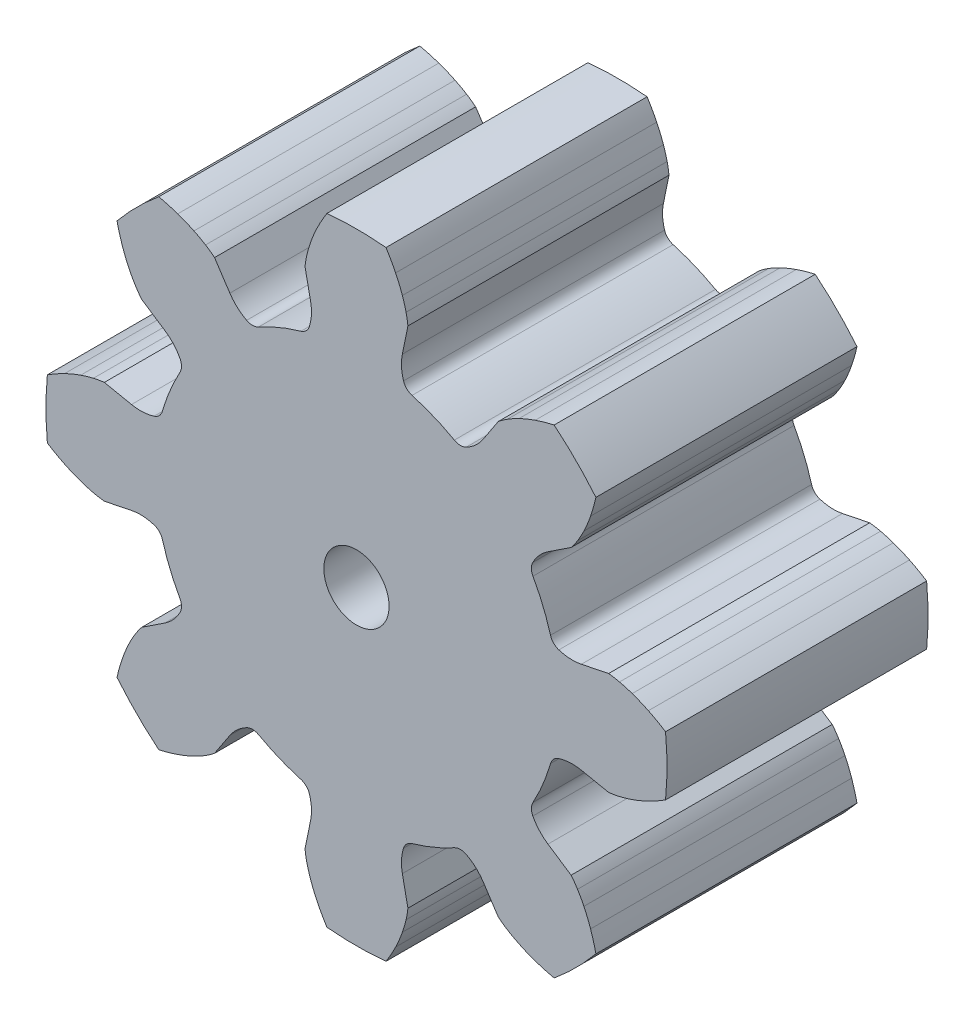
SolidWorks part; units mm, degrees
ref_plane "Front Plane" through (0, 0, 0) normal (0, 0, 1) x (1, 0, 0)
ref_plane "Top Plane" through (0, 0, 0) normal (0, 1, 0) x (1, 0, 0)
ref_plane "Right Plane" through (0, 0, 0) normal (1, 0, 0) x (0, 0, -1)
sketch "Model" plane through (0, 0, 0) normal (0, 0, 1) x (1, 0, 0)
  line L0 (10.9417, -2.2327) -> (12.2644, -2.5026)
  line L1 (12.2644, 2.5026) -> (10.9417, 2.2327)
  line L2 (9.3157, 6.1582) -> (10.4419, 6.9027)
  line L3 (6.9027, 10.4419) -> (6.1582, 9.3157)
  line L4 (2.2327, 10.9417) -> (2.5026, 12.2644)
  line L5 (-2.5026, 12.2644) -> (-2.2327, 10.9417)
  line L6 (-6.1582, 9.3157) -> (-6.9027, 10.4419)
  line L7 (-10.4419, 6.9027) -> (-9.3157, 6.1582)
  line L8 (-10.9417, 2.2327) -> (-12.2644, 2.5026)
  line L9 (-12.2644, -2.5026) -> (-10.9417, -2.2327)
  line L10 (-9.3157, -6.1582) -> (-10.4419, -6.9027)
  line L11 (-6.9027, -10.4419) -> (-6.1582, -9.3157)
  line L12 (-2.2327, -10.9417) -> (-2.5026, -12.2644)
  line L13 (2.5026, -12.2644) -> (2.2327, -10.9417)
  line L14 (6.1582, -9.3157) -> (6.9027, -10.4419)
  line L15 (10.4419, -6.9027) -> (9.3157, -6.1582)
  arc A1 (9.072, -3.7577) -> (9.44, -2.7033) centre (0, 0) ccw
  arc A2 (9.8442, -2.2889) -> (9.44, -2.7033) centre (10.0267, -2.8713) ccw
  arc A3 (10.9417, -2.2327) -> (9.8442, -2.2889) centre (10.502, -4.3879) ccw
  arc A4 (12.2644, -2.5026) -> (12.7952, -2.4127) centre (11.8124, 1.7812) ccw
  arc A5 (12.7952, -2.4127) -> (13.4129, -2.2334) centre (11.3922, 3.5743) ccw
  arc A6 (13.4129, -2.2334) -> (14.2001, -1.9047) centre (11.1046, 4.4008) ccw
  arc A7 (14.2001, -1.9047) -> (15.0358, -1.4368) centre (10.2968, 6.0465) ccw
  arc A8 (15.0358, -1.4368) -> (15.0358, 1.4368) centre (0, 0) ccw
  arc A9 (15.0358, 1.4368) -> (14.2001, 1.9047) centre (10.2968, -6.0465) ccw
  arc A10 (14.2001, 1.9047) -> (13.4129, 2.2334) centre (11.1046, -4.4008) ccw
  arc A11 (13.4129, 2.2334) -> (12.7952, 2.4127) centre (11.3922, -3.5743) ccw
  arc A12 (12.7952, 2.4127) -> (12.2644, 2.5026) centre (11.8124, -1.7812) ccw
  arc A13 (9.8442, 2.2889) -> (10.9417, 2.2327) centre (10.502, 4.3879) ccw
  arc A14 (9.44, 2.7033) -> (9.8442, 2.2889) centre (10.0267, 2.8713) ccw
  arc A15 (9.44, 2.7033) -> (8.5866, 4.7635) centre (0, 0) ccw
  arc A16 (8.5794, 5.3424) -> (8.5866, 4.7635) centre (9.1203, 5.0596) ccw
  arc A17 (9.3157, 6.1582) -> (8.5794, 5.3424) centre (10.5287, 4.3233) ccw
  arc A18 (10.4419, 6.9027) -> (10.7537, 7.3415) centre (7.0931, 9.6121) ccw
  arc A19 (10.7537, 7.3415) -> (11.0637, 7.9051) centre (5.5281, 10.5829) ccw
  arc A20 (11.0637, 7.9051) -> (11.3878, 8.6941) centre (4.7403, 10.964) ccw
  arc A21 (11.3878, 8.6941) -> (11.6479, 9.616) centre (3.0054, 11.5564) ccw
  arc A22 (11.6479, 9.616) -> (9.616, 11.6479) centre (0, 0) ccw
  arc A23 (9.616, 11.6479) -> (8.6941, 11.3878) centre (11.5564, 3.0054) ccw
  arc A24 (8.6941, 11.3878) -> (7.9051, 11.0637) centre (10.964, 4.7403) ccw
  arc A25 (7.9051, 11.0637) -> (7.3415, 10.7537) centre (10.5829, 5.5281) ccw
  arc A26 (7.3415, 10.7537) -> (6.9027, 10.4419) centre (9.6121, 7.0931) ccw
  arc A27 (5.3424, 8.5794) -> (6.1582, 9.3157) centre (4.3233, 10.5287) ccw
  arc A28 (4.7635, 8.5866) -> (5.3424, 8.5794) centre (5.0596, 9.1203) ccw
  arc A29 (4.7635, 8.5866) -> (2.7033, 9.44) centre (0, 0) ccw
  arc A30 (2.2889, 9.8442) -> (2.7033, 9.44) centre (2.8713, 10.0267) ccw
  arc A31 (2.2327, 10.9417) -> (2.2889, 9.8442) centre (4.3879, 10.502) ccw
  arc A32 (2.5026, 12.2644) -> (2.4127, 12.7952) centre (-1.7812, 11.8124) ccw
  arc A33 (2.4127, 12.7952) -> (2.2334, 13.4129) centre (-3.5743, 11.3922) ccw
  arc A34 (2.2334, 13.4129) -> (1.9047, 14.2001) centre (-4.4008, 11.1046) ccw
  arc A35 (1.9047, 14.2001) -> (1.4368, 15.0358) centre (-6.0465, 10.2968) ccw
  arc A36 (1.4368, 15.0358) -> (-1.4368, 15.0358) centre (0, 0) ccw
  arc A37 (-1.4368, 15.0358) -> (-1.9047, 14.2001) centre (6.0465, 10.2968) ccw
  arc A38 (-1.9047, 14.2001) -> (-2.2334, 13.4129) centre (4.4008, 11.1046) ccw
  arc A39 (-2.2334, 13.4129) -> (-2.4127, 12.7952) centre (3.5743, 11.3922) ccw
  arc A40 (-2.4127, 12.7952) -> (-2.5026, 12.2644) centre (1.7812, 11.8124) ccw
  arc A41 (-2.2889, 9.8442) -> (-2.2327, 10.9417) centre (-4.3879, 10.502) ccw
  arc A42 (-2.7033, 9.44) -> (-2.2889, 9.8442) centre (-2.8713, 10.0267) ccw
  arc A43 (-2.7033, 9.44) -> (-4.7635, 8.5866) centre (0, 0) ccw
  arc A44 (-5.3424, 8.5794) -> (-4.7635, 8.5866) centre (-5.0596, 9.1203) ccw
  arc A45 (-6.1582, 9.3157) -> (-5.3424, 8.5794) centre (-4.3233, 10.5287) ccw
  arc A46 (-6.9027, 10.4419) -> (-7.3415, 10.7537) centre (-9.6121, 7.0931) ccw
  arc A47 (-7.3415, 10.7537) -> (-7.9051, 11.0637) centre (-10.5829, 5.5281) ccw
  arc A48 (-7.9051, 11.0637) -> (-8.6941, 11.3878) centre (-10.964, 4.7403) ccw
  arc A49 (-8.6941, 11.3878) -> (-9.616, 11.6479) centre (-11.5564, 3.0054) ccw
  arc A50 (-9.616, 11.6479) -> (-11.6479, 9.616) centre (0, 0) ccw
  arc A51 (-11.6479, 9.616) -> (-11.3878, 8.6941) centre (-3.0054, 11.5564) ccw
  arc A52 (-11.3878, 8.6941) -> (-11.0637, 7.9051) centre (-4.7403, 10.964) ccw
  arc A53 (-11.0637, 7.9051) -> (-10.7537, 7.3415) centre (-5.5281, 10.5829) ccw
  arc A54 (-10.7537, 7.3415) -> (-10.4419, 6.9027) centre (-7.0931, 9.6121) ccw
  arc A55 (-8.5794, 5.3424) -> (-9.3157, 6.1582) centre (-10.5287, 4.3233) ccw
  arc A56 (-8.5866, 4.7635) -> (-8.5794, 5.3424) centre (-9.1203, 5.0596) ccw
  arc A57 (-8.5866, 4.7635) -> (-9.44, 2.7033) centre (0, 0) ccw
  arc A58 (-9.8442, 2.2889) -> (-9.44, 2.7033) centre (-10.0267, 2.8713) ccw
  arc A59 (-10.9417, 2.2327) -> (-9.8442, 2.2889) centre (-10.502, 4.3879) ccw
  arc A60 (-12.2644, 2.5026) -> (-12.7952, 2.4127) centre (-11.8124, -1.7812) ccw
  arc A61 (-12.7952, 2.4127) -> (-13.4129, 2.2334) centre (-11.3922, -3.5743) ccw
  arc A62 (-13.4129, 2.2334) -> (-14.2001, 1.9047) centre (-11.1046, -4.4008) ccw
  arc A63 (-14.2001, 1.9047) -> (-15.0358, 1.4368) centre (-10.2968, -6.0465) ccw
  arc A64 (-15.0358, 1.4368) -> (-15.0358, -1.4368) centre (0, 0) ccw
  arc A65 (-15.0358, -1.4368) -> (-14.2001, -1.9047) centre (-10.2968, 6.0465) ccw
  arc A66 (-14.2001, -1.9047) -> (-13.4129, -2.2334) centre (-11.1046, 4.4008) ccw
  arc A67 (-13.4129, -2.2334) -> (-12.7952, -2.4127) centre (-11.3922, 3.5743) ccw
  arc A68 (-12.7952, -2.4127) -> (-12.2644, -2.5026) centre (-11.8124, 1.7812) ccw
  arc A69 (-9.8442, -2.2889) -> (-10.9417, -2.2327) centre (-10.502, -4.3879) ccw
  arc A70 (-9.44, -2.7033) -> (-9.8442, -2.2889) centre (-10.0267, -2.8713) ccw
  arc A71 (-9.44, -2.7033) -> (-8.5866, -4.7635) centre (0, 0) ccw
  arc A72 (-8.5794, -5.3424) -> (-8.5866, -4.7635) centre (-9.1203, -5.0596) ccw
  arc A73 (-9.3157, -6.1582) -> (-8.5794, -5.3424) centre (-10.5287, -4.3233) ccw
  arc A74 (-10.4419, -6.9027) -> (-10.7537, -7.3415) centre (-7.0931, -9.6121) ccw
  arc A75 (-10.7537, -7.3415) -> (-11.0637, -7.9051) centre (-5.5281, -10.5829) ccw
  arc A76 (-11.0637, -7.9051) -> (-11.3878, -8.6941) centre (-4.7403, -10.964) ccw
  arc A77 (-11.3878, -8.6941) -> (-11.6479, -9.616) centre (-3.0054, -11.5564) ccw
  arc A78 (-11.6479, -9.616) -> (-9.616, -11.6479) centre (0, 0) ccw
  arc A79 (-9.616, -11.6479) -> (-8.6941, -11.3878) centre (-11.5564, -3.0054) ccw
  arc A80 (-8.6941, -11.3878) -> (-7.9051, -11.0637) centre (-10.964, -4.7403) ccw
  arc A81 (-7.9051, -11.0637) -> (-7.3415, -10.7537) centre (-10.5829, -5.5281) ccw
  arc A82 (-7.3415, -10.7537) -> (-6.9027, -10.4419) centre (-9.6121, -7.0931) ccw
  arc A83 (-5.3424, -8.5794) -> (-6.1582, -9.3157) centre (-4.3233, -10.5287) ccw
  arc A84 (-4.7635, -8.5866) -> (-5.3424, -8.5794) centre (-5.0596, -9.1203) ccw
  arc A85 (-4.7635, -8.5866) -> (-2.7033, -9.44) centre (0, 0) ccw
  arc A86 (-2.2889, -9.8442) -> (-2.7033, -9.44) centre (-2.8713, -10.0267) ccw
  arc A87 (-2.2327, -10.9417) -> (-2.2889, -9.8442) centre (-4.3879, -10.502) ccw
  arc A88 (-2.5026, -12.2644) -> (-2.4127, -12.7952) centre (1.7812, -11.8124) ccw
  arc A89 (-2.4127, -12.7952) -> (-2.2334, -13.4129) centre (3.5743, -11.3922) ccw
  arc A90 (-2.2334, -13.4129) -> (-1.9047, -14.2001) centre (4.4008, -11.1046) ccw
  arc A91 (-1.9047, -14.2001) -> (-1.4368, -15.0358) centre (6.0465, -10.2968) ccw
  arc A92 (-1.4368, -15.0358) -> (1.4368, -15.0358) centre (0, 0) ccw
  arc A93 (1.4368, -15.0358) -> (1.9047, -14.2001) centre (-6.0465, -10.2968) ccw
  arc A94 (1.9047, -14.2001) -> (2.2334, -13.4129) centre (-4.4008, -11.1046) ccw
  arc A95 (2.2334, -13.4129) -> (2.4127, -12.7952) centre (-3.5743, -11.3922) ccw
  arc A96 (2.4127, -12.7952) -> (2.5026, -12.2644) centre (-1.7812, -11.8124) ccw
  arc A97 (2.2889, -9.8442) -> (2.2327, -10.9417) centre (4.3879, -10.502) ccw
  arc A98 (2.7033, -9.44) -> (2.2889, -9.8442) centre (2.8713, -10.0267) ccw
  arc A99 (2.7033, -9.44) -> (4.7635, -8.5866) centre (0, 0) ccw
  arc A100 (5.3424, -8.5794) -> (4.7635, -8.5866) centre (5.0596, -9.1203) ccw
  arc A101 (6.1582, -9.3157) -> (5.3424, -8.5794) centre (4.3233, -10.5287) ccw
  arc A102 (6.9027, -10.4419) -> (7.3415, -10.7537) centre (9.6121, -7.0931) ccw
  arc A103 (7.3415, -10.7537) -> (7.9051, -11.0637) centre (10.5829, -5.5281) ccw
  arc A104 (7.9051, -11.0637) -> (8.6941, -11.3878) centre (10.964, -4.7403) ccw
  arc A105 (8.6941, -11.3878) -> (9.616, -11.6479) centre (11.5564, -3.0054) ccw
  arc A106 (9.616, -11.6479) -> (11.6479, -9.616) centre (0, 0) ccw
  arc A107 (11.6479, -9.616) -> (11.3878, -8.6941) centre (3.0054, -11.5564) ccw
  arc A108 (11.3878, -8.6941) -> (11.0637, -7.9051) centre (4.7403, -10.964) ccw
  arc A109 (11.0637, -7.9051) -> (10.7537, -7.3415) centre (5.5281, -10.5829) ccw
  arc A110 (10.7537, -7.3415) -> (10.4419, -6.9027) centre (7.0931, -9.6121) ccw
  arc A111 (8.5794, -5.3424) -> (9.3157, -6.1582) centre (10.5287, -4.3233) ccw
  arc A112 (8.5866, -4.7635) -> (8.5794, -5.3424) centre (9.1203, -5.0596) ccw
  arc A113 (8.5866, -4.7635) -> (9.072, -3.7577) centre (0, 0) ccw
extrude "Boss-Extrude1" add sketch "Model" along normal blind 12.7
sketch "Sketch2" plane through (0, 0, 12.7) normal (0, 0, 1) x (1, 0, 0)
  circle A0 centre (0, 0) radius 1.5875
  dimension "D1" = 3.175
extrude "Cut-Extrude1" cut sketch "Sketch2" against normal through all
